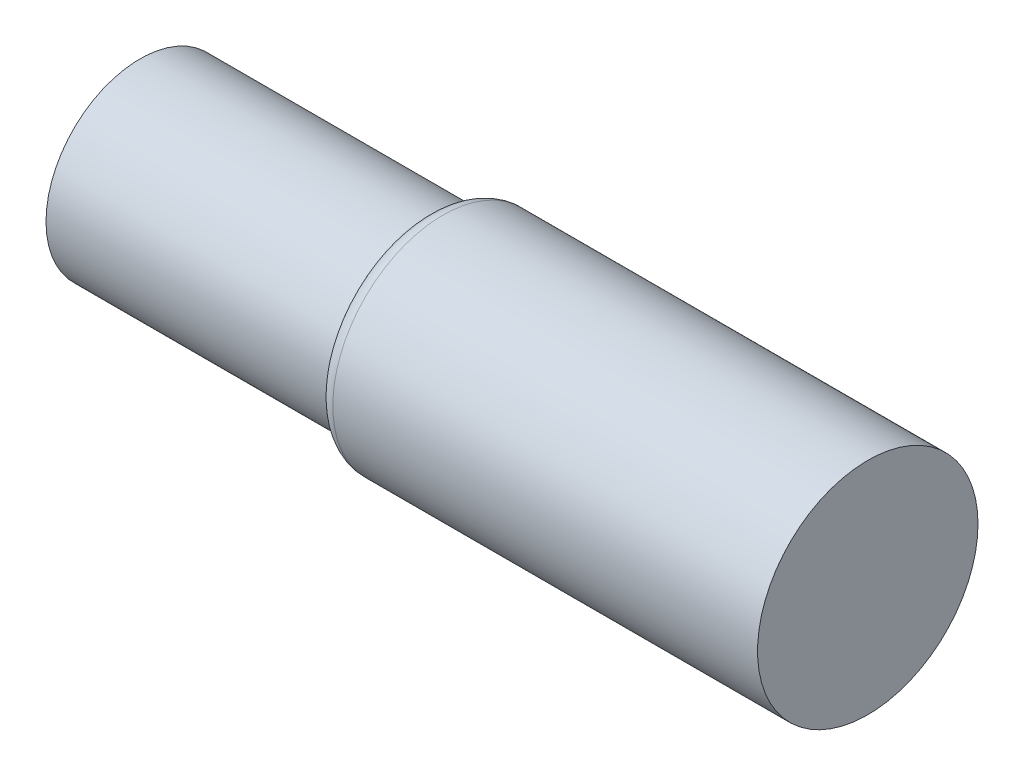
SolidWorks part; units mm, degrees
ref_plane "前视基准面" through (0, 0, 0) normal (0, 0, 1) x (1, 0, 0)
ref_plane "上视基准面" through (0, 0, 0) normal (0, 1, 0) x (1, 0, 0)
ref_plane "右视基准面" through (0, 0, 0) normal (1, 0, 0) x (0, 0, -1)
sketch "Sketch2" plane through (0, 0, 0) normal (1, 0, 0) x (0, 0, -1)
  circle A0 centre (0, 0) radius 16
  dimension "D1" = 32
extrude "Boss-Extrude1" add sketch "Sketch2" along normal blind 48.8
sketch "Sketch3" plane through (48.8, 0, 0) normal (1, 0, 0) x (0, 0, -1)
  circle A0 centre (0, 0) radius 18.75
  dimension "D1" = 37.5
extrude "Boss-Extrude2" add sketch "Sketch3" along normal blind 75
fillet "Fillet1" radius 2.74 1 edges at (48.8, 0, -18.75)
sketch "Sketch4" plane through (0, 0, 0) normal (-1, 0, 0) x (0, 0, 1)
  circle A0 centre (0, 0) radius 3
extrude "Cut-Extrude1" cut sketch "Sketch4" against normal blind 2
sketch "Sketch5" plane through (0, 0, 0) normal (-1, 0, 0) x (0, 0, 1)
  line L0 (-16, 0) -> (16, 0) construction
  line L1 (0, 16.01) -> (0, -16) construction
  circle A0 centre (0, 0) radius 16 construction
  circle A1 centre (0, 0) radius 16.01 construction
  circle A2 centre (-8, 8) radius 2
  circle A3 centre (8, 8) radius 2
  circle A4 centre (8, -8) radius 2
  circle A5 centre (-8, -8) radius 2
  dimension "D1" = 8
  dimension "D2" = 8
extrude "Cut-Extrude2" cut sketch "Sketch5" against normal blind 10
